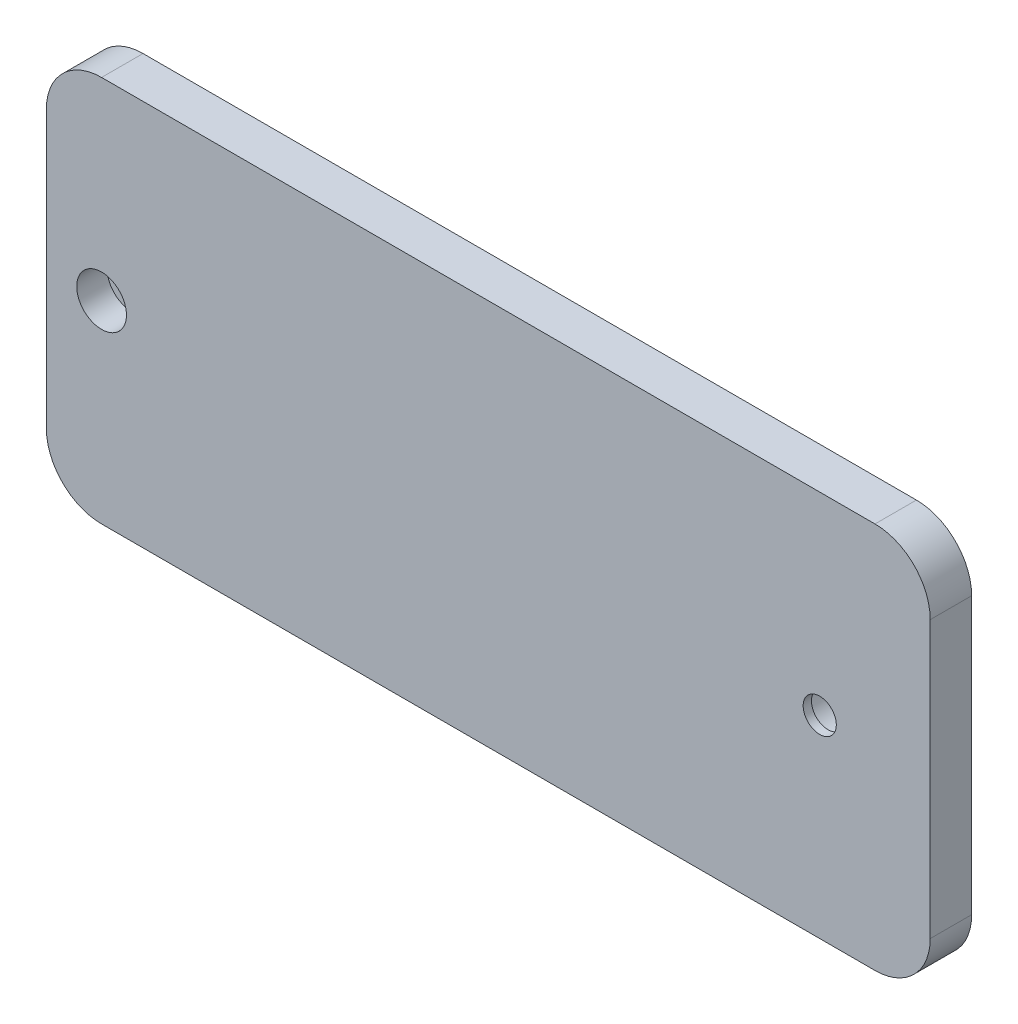
SolidWorks part; units mm, degrees
material "Polylactide (PLA)"
ref_plane "Front Plane" through (0, 0, 0) normal (0, 0, 1) x (1, 0, 0)
ref_plane "Top Plane" through (0, 0, 0) normal (0, 1, 0) x (1, 0, 0)
ref_plane "Right Plane" through (0, 0, 0) normal (1, 0, 0) x (0, 0, -1)
sketch "Sketch1" plane through (0, 0, 0) normal (0, 0, 1) x (1, 0, 0)
  line L1 (-80, 35) -> (80, 35)
  line L2 (-80, 35) -> (-80, -35)
  line L3 (-80, -35) -> (80, -35)
  line L4 (80, 35) -> (80, -35)
  point P4 (0, 35)
  point P6 (-80, 0)
  dimension "D1" = 160
  dimension "D2" = 70
extrude "Boss-Extrude1" add sketch "Sketch1" along normal blind 7.5
sketch "Sketch2" plane through (0, 0, 7.5) normal (0, 0, 1) x (1, 0, 0)
  line L0 (-80, 35) -> (-80, -35) construction
  line L1 (80, -35) -> (80, 35) construction
  circle A0 centre (-70, 0) radius 2.5
  circle A1 centre (60, 0) radius 3
  dimension "D1" = 5
  dimension "D2" = 6
  dimension "D3" = 10
  dimension "D4" = 20
extrude "Cut-Extrude1" cut sketch "Sketch2" against normal through all both and the other way through all
sketch "Sketch3" plane through (0, 0, 7.5) normal (0, 0, 1) x (1, 0, 0)
  circle A0 centre (-70, 0) radius 4.5
  dimension "D1" = 9
extrude "Cut-Extrude2" cut sketch "Sketch3" against normal blind 5.5
sketch "Sketch4" plane through (0, 0, 0) normal (0, 0, -1) x (-1, 0, 0)
  circle A0 centre (-60, 0) radius 5
  dimension "D1" = 10
extrude "Cut-Extrude3" cut sketch "Sketch4" against normal blind 6
sketch "Sketch5" plane through (0, 0, 0) normal (0, 0, -1) x (-1, 0, 0)
  line L1 (-35, 2.5) -> (60, 2.5)
  line L2 (-35, 2.5) -> (-35, -2.5)
  line L3 (-35, -2.5) -> (60, -2.5)
  line L4 (60, 2.5) -> (60, -2.5)
  circle A0 centre (-60, 0) radius 3 construction
  point P4 (-35, 0)
  dimension "D3" = 25
  dimension "D1" = 5
  dimension "D2" = 95
extrude "Boss-Extrude2" add sketch "Sketch5" along normal blind 2.3
sketch "Sketch6" plane through (35, 0, 0) normal (1, 0, 0) x (0, 0, -1)
  line L0 (2.3, 6) -> (2.3, -6)
  line L2 (2.3, 6) -> (6.6, 2.5)
  line L3 (6.6, 2.5) -> (6.6, -2.5)
  line L4 (6.6, -2.5) -> (2.3, -6)
  point P0 (6.6, 0)
  point P3 (2.3, 0)
  dimension "D1" = 12
  dimension "D2" = 5
  dimension "D3" = 4.3
extrude "Boss-Extrude3" add sketch "Sketch6" against normal blind 95
fillet "Fillet1" radius 1 2 edges at (-12.5, -2.5, -6.6) (-12.5, 2.5, -6.6)
fillet "Fillet2" radius 0.5 2 edges at (-12.5, -6, -2.3) (-12.5, 6, -2.3)
fillet "Fillet3" radius 10 4 edges at (-80, 35, 3.75) (-80, -35, 3.75) (80, -35, 3.75) (80, 35, 3.75)
